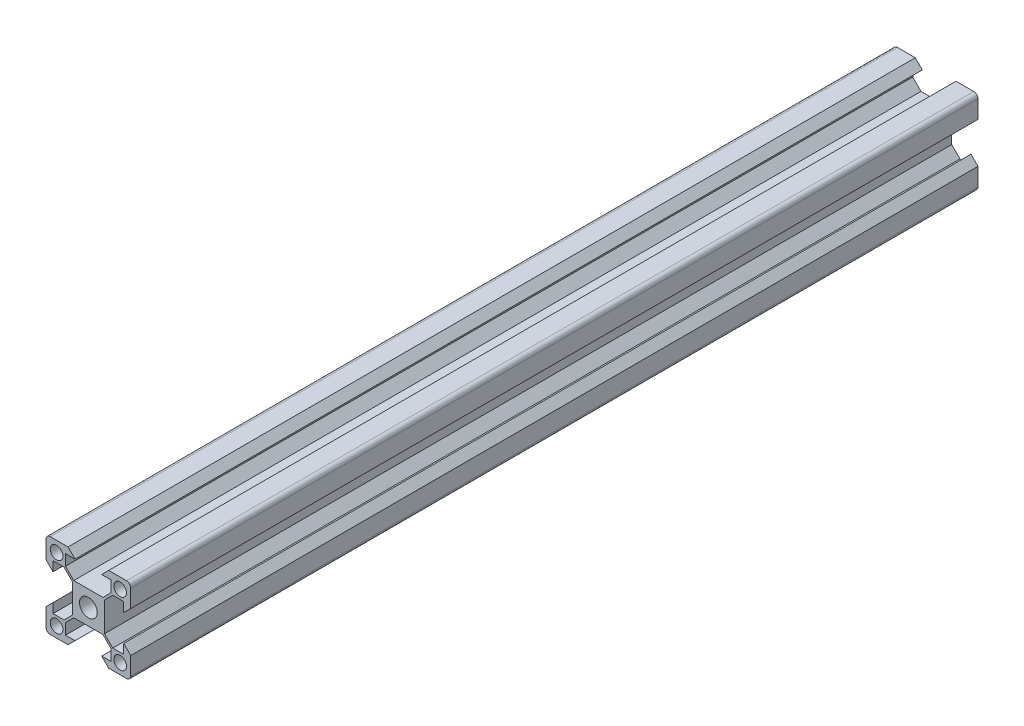
SolidWorks part; units mm, degrees
material "铝管"
ref_plane "前视基准面" through (0, 0, 0) normal (0, 0, 1) x (1, 0, 0)
ref_plane "上视基准面" through (0, 0, 0) normal (0, 1, 0) x (1, 0, 0)
ref_plane "右视基准面" through (0, 0, 0) normal (1, 0, 0) x (0, 0, -1)
sketch "草图1" plane through (0, 0, 0) normal (0, 0, 1) x (1, 0, 0)
  line L0 (0, 0) -> (-40.5659, 40.5659) construction
  line L1 (0, 0) -> (0, 75.5033) construction
  line L2 (-10, 10) -> (-10, 4.8)
  line L3 (-10, 4.8) -> (-8.34, 3.14)
  line L4 (-8.34, 3.14) -> (-8.34, 5.4)
  line L5 (-5.7536, 5.4) -> (-3.8, 3.4464)
  line L6 (-3.8, 3.4464) -> (-3.8, -3.4464)
  line L7 (-3.8, 0) -> (15.6715, 0) construction
  line L8 (-5.4, 8.34) -> (-5.4, 5.7536)
  line L9 (-3.4464, 3.8) -> (3.4464, 3.8)
  line L10 (-5.4, 5.7536) -> (-3.4464, 3.8)
  line L11 (-3.14, 8.34) -> (-5.4, 8.34)
  line L12 (-8.34, 5.4) -> (-5.7536, 5.4)
  line L13 (-4.8, 10) -> (-3.14, 8.34)
  line L14 (-10, 10) -> (-4.8, 10)
  line L15 (-10, -10) -> (-4.8, -10)
  line L16 (-4.8, -10) -> (-3.14, -8.34)
  line L17 (-8.34, -5.4) -> (-5.7536, -5.4)
  line L18 (-3.14, -8.34) -> (-5.4, -8.34)
  line L19 (-5.4, -5.7536) -> (-3.4464, -3.8)
  line L20 (-3.4464, -3.8) -> (3.4464, -3.8)
  line L21 (-5.4, -8.34) -> (-5.4, -5.7536)
  line L22 (-5.7536, -5.4) -> (-3.8, -3.4464)
  line L23 (-8.34, -3.14) -> (-8.34, -5.4)
  line L24 (-10, -4.8) -> (-8.34, -3.14)
  line L25 (-10, -10) -> (-10, -4.8)
  line L26 (10, -10) -> (10, -4.8)
  line L27 (10, -4.8) -> (8.34, -3.14)
  line L28 (8.34, -3.14) -> (8.34, -5.4)
  line L29 (5.7536, -5.4) -> (3.8, -3.4464)
  line L30 (5.4, -8.34) -> (5.4, -5.7536)
  line L31 (5.4, -5.7536) -> (3.4464, -3.8)
  line L32 (3.14, -8.34) -> (5.4, -8.34)
  line L33 (8.34, -5.4) -> (5.7536, -5.4)
  line L34 (4.8, -10) -> (3.14, -8.34)
  line L35 (10, -10) -> (4.8, -10)
  line L36 (10, 10) -> (4.8, 10)
  line L37 (4.8, 10) -> (3.14, 8.34)
  line L38 (8.34, 5.4) -> (5.7536, 5.4)
  line L39 (3.14, 8.34) -> (5.4, 8.34)
  line L40 (5.4, 5.7536) -> (3.4464, 3.8)
  line L41 (5.4, 8.34) -> (5.4, 5.7536)
  line L42 (3.8, 3.4464) -> (3.8, -3.4464)
  line L43 (5.7536, 5.4) -> (3.8, 3.4464)
  line L44 (8.34, 3.14) -> (8.34, 5.4)
  line L45 (10, 4.8) -> (8.34, 3.14)
  line L46 (10, 10) -> (10, 4.8)
  circle A0 centre (-7.5, 7.5) radius 1.5
  circle A1 centre (0, 0) radius 2.1
  circle A2 centre (-7.5, -7.5) radius 1.5
  circle A3 centre (7.5, -7.5) radius 1.5
  circle A4 centre (7.5, 7.5) radius 1.5
  point P54 (0, -3.8)
  point P64 (0, 3.8)
  dimension "D6" = 3
  dimension "D7" = 7.5
  dimension "D9" = 4.2
  dimension "D1" = 45
  dimension "D2" = 4.8
  dimension "D3" = 3.8
  dimension "D4" = 10
  dimension "D5" = 5.4
  dimension "D8" = 3.14
  dimension "D10" = 10
  dimension "D11" = 0.5
extrude "凸台-拉伸1" add sketch "草图1" along normal mid plane 200
fillet "圆角1" radius 1 4 edges at (-10, -10, 0) (10, -10, 0) (-10, 10, 0) (10, 10, 0)
